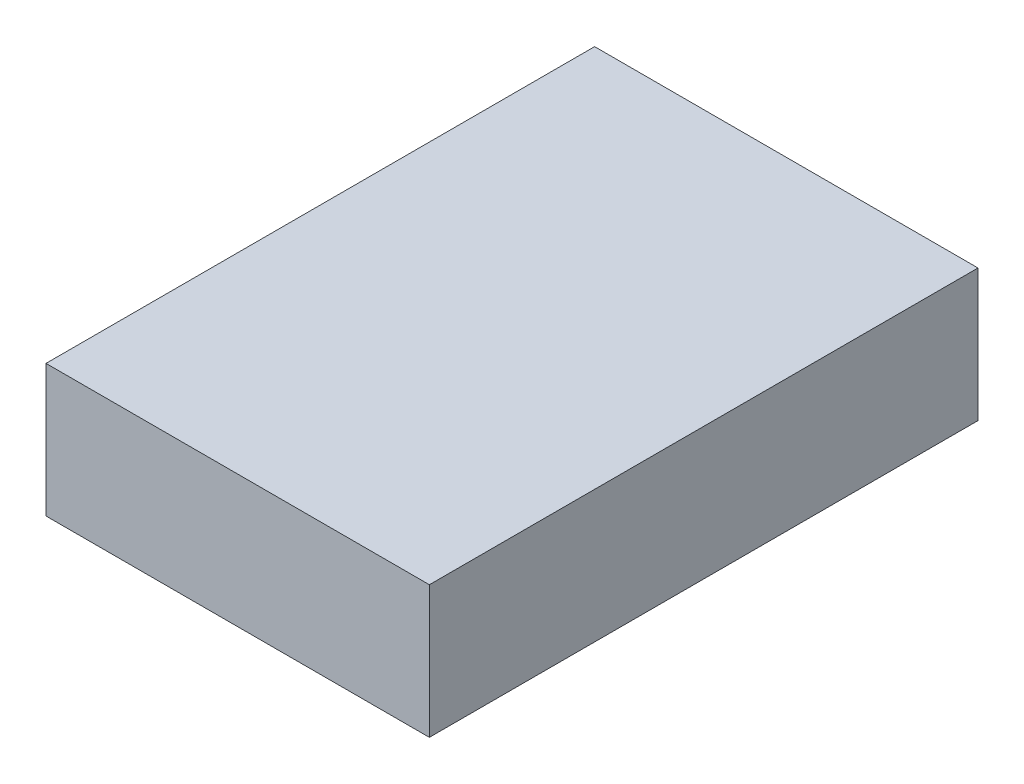
SolidWorks part; units mm, degrees
ref_plane "Front Plane" through (0, 0, 0) normal (0, 0, 1) x (1, 0, 0)
ref_plane "Top Plane" through (0, 0, 0) normal (0, 1, 0) x (1, 0, 0)
ref_plane "Right Plane" through (0, 0, 0) normal (1, 0, 0) x (0, 0, -1)
sketch "Sketch1" plane through (0, 0, 0) normal (0, 1, 0) x (1, 0, 0)
  line L1 (-33.3734, 15.2781) -> (24.6266, 15.2781)
  line L2 (-33.3734, 15.2781) -> (-33.3734, -67.7219)
  line L3 (-33.3734, -67.7219) -> (24.6266, -67.7219)
  line L4 (24.6266, 15.2781) -> (24.6266, -67.7219)
  dimension "D1" = 83
  dimension "D2" = 58
extrude "Boss-Extrude1" add sketch "Sketch1" along normal blind 20
